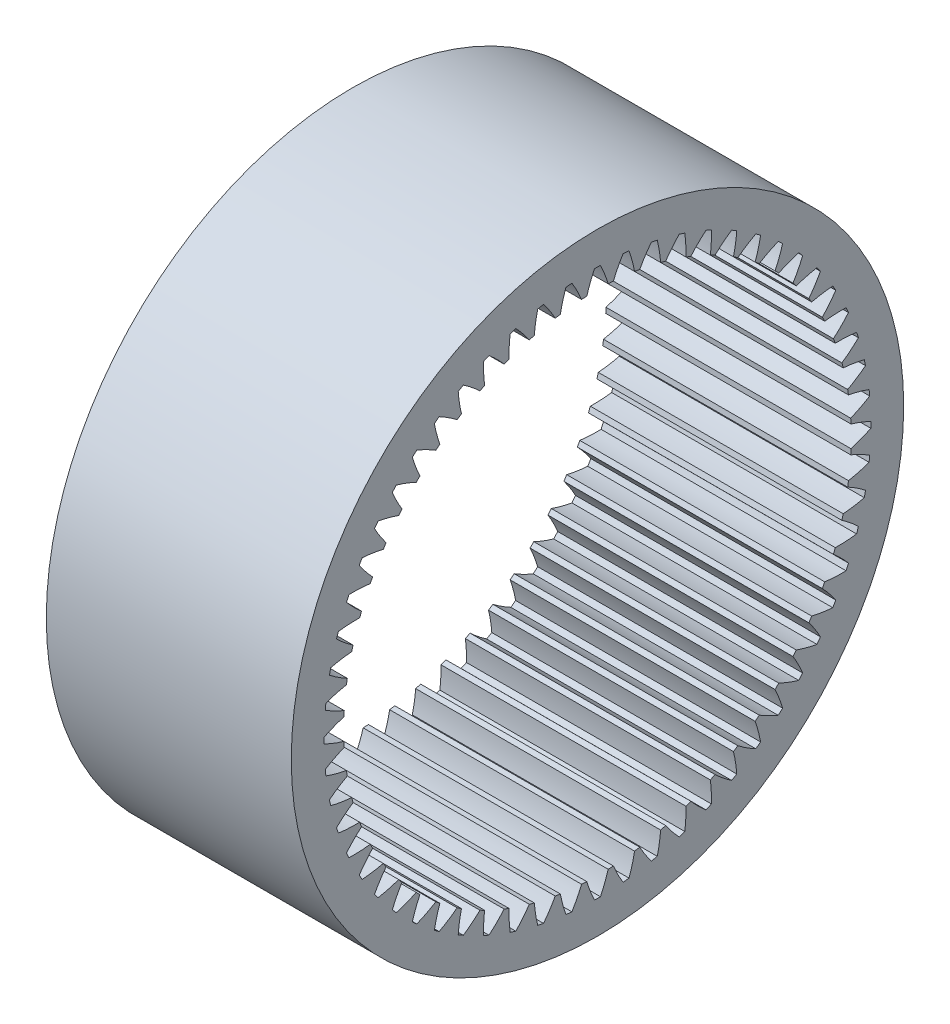
SolidWorks part; units mm, degrees
ref_plane "Plane1" through (0, 0, 0) normal (0, 0, 1) x (1, 0, 0)
ref_plane "Plane2" through (0, 0, 0) normal (0, 1, 0) x (1, 0, 0)
ref_plane "Plane3" through (0, 0, 0) normal (1, 0, 0) x (0, 0, -1)
other "Configuration Table"
sketch "HoldingSke" plane through (0, 0, 0) normal (0, 1, 0) x (1, 0, 0)
  line L0 (0, 0) -> (0.5, -0.866)
  line L1 (-15, 0) -> (100, 0) construction
  line L2 (0, 0) -> (-2.1039, 2.3779)
  line L3 (0, 0) -> (-11.863, 4.5341)
  line L4 (0, 0) -> (4.318, 7.479)
  line L5 (0, 0) -> (-23.7986, -8.8762)
  line L6 (0, 0) -> (-10.5278, -7.1032)
  line L7 (-2.1039, 2.3779) -> (3.3635, 27.1825)
  line L8 (-76.2, 3.3779) -> (-54.61, 3.3779)
  line L9 (-71.009, 38.7566) -> (-53.1078, 45.2721)
  line L10 (-76.2, 71.12) -> (104.1128, 71.12)
  line L11 (0, 0) -> (-28, 0)
  line L12 (-76.2, 101.6) -> (-76.162, 101.6)
  line L13 (24.9733, 27.94) -> (52.9518, 28.4284)
  line L14 (24.9733, 27.94) -> (24.9743, 27.94)
  line L15 (24.9733, 27.94) -> (100.4006, 29.5858)
  circle A0 centre (0, 0) radius 35
  circle A1 centre (0, 0) radius 12.7
  circle A2 centre (0, 0) radius 12.7
  dimension "MHD" = 25.4
  dimension "Hub_dia" = 25.4
  dimension "Diameter" = 70
  dimension "Num_teeth" = 60
  dimension "Pitch" = 1
  dimension "Overall_len" = 25.4
  dimension "Show_teeth" = 60
  dimension "Thickness" = 12.7
  dimension "OAL" = 25.4001
  dimension "T_dim" = 21.59
  dimension "Ap" = 20
  dimension "H" = 19.05
  dimension "Pitch_radius" = 180.3128
  dimension "Width" = 28
  dimension "Backlash" = 0.038
  dimension "Addendum_fac" = 1
  dimension "Dedendum_fac" = 1.25
  dimension "Clearance_fac" = 0.25
  dimension "Dedendum_add" = 0.001
  dimension "Module" = 1
sketch "BasProSke" plane through (0, 0, 0) normal (0, 1, 0) x (1, 0, 0)
  line L0 (-10, 0) -> (60, 0) construction
  line L1 (0, 29) -> (0, 35)
  line L2 (0, 29) -> (28, 29)
  line L3 (28, 29) -> (28, 35)
  line L4 (28, 35) -> (0, 35)
  dimension "Diameter" = 70
  dimension "Thickness" = 28
  dimension "Inside_diameter" = 58
revolve "Base-Revolve" add sketch "BasProSke" angle 360 about L0
sketch "TooCutSke" plane through (0, 0, 0) normal (1, 0, 0) x (0, 0, -1)
  line L3 (0.8803, 29.9871) -> (0.8803, 53.6633) construction
  line L4 (0, 0) -> (0, 59.563) construction
  line L5 (0, 0) -> (-3.576, 68.2339) construction
  line L6 (-13.1633, 24.7167) -> (36.4631, 27.3175) construction
  circle A0 centre (0, 0) radius 30 construction
  circle A1 centre (0, 0) radius 31.251 construction
  circle A2 centre (0, 0) radius 25.3717 construction
  circle A3 centre (0, 0) radius 28.9746 construction
  arc A4 (1.2274, 28.9486) -> (0.3395, 31.2492) centre (-13.1633, 24.7167) ccw
  arc A5 (1.2274, 28.9486) -> (-1.2274, 28.9486) centre (0, 0) ccw
  arc A6 (0.3395, 31.2492) -> (-0.3395, 31.2492) centre (0, 0) ccw
  arc A7 (-0.3395, 31.2492) -> (-1.2274, 28.9486) centre (13.1633, 24.7167) ccw
  dimension "Pitch_dia" = 60
  dimension "Base_dia" = 50.7434
  dimension "Root_dia" = 62.502
  dimension "Overcut_dia" = 57.9492
  dimension "Flank_rad" = 15
  dimension "Half_ang" = 3
  dimension "Half_CT" = 0.8803
extrude "ToothCut" cut sketch "TooCutSke" along normal through all
fillet "Breaks" [suppressed] radius 0.1
fillet "RootFillets" [suppressed] radius 0.251
pattern_circular "TeethCuts" count 60 every 6 about axis through (-10, 0, 0) along (1, 0, 0) of "RootFillets", "Breaks", "ToothCut"
equation "' \"Module@HoldingSke\" = 6.35"
equation "' \"Num_teeth@HoldingSke\" = 24"
equation "' \"Ap@HoldingSke\" =  14.5"
equation "' \"Ap@HoldingSke\" = 14.5"
equation "' \"Width@HoldingSke\" = 12"
equation "' \"Diameter@HoldingSke\" = 8 * 25.4"
equation "' \"Show_teeth@HoldingSke\" = 100"
equation "' \"Backlash@HoldingSke\" = 0.009 * 25.4"
equation "' \"Addendum_fac@HoldingSke\" = 1.0"
equation "' \"Dedendum_fac@HoldingSke\" = 1.25"
equation "' \"Dedendum_add@HoldingSke\" = 0.00005 * 25.4"
equation "' \"Clearance_fac@HoldingSke\" = 0.25"
equation "\"Pitch@HoldingSke\" = 1 / \"Module@HoldingSke\" "
equation "\"Overcut_dia@TooCutSke\" = (\"Num_teeth@HoldingSke\" - 2 * \"Addendum_fac@HoldingSke\") / \"Pitch@HoldingSke\" - 0.002 * 25.4"
equation "\"Pitch_dia@TooCutSke\" = \"Num_teeth@HoldingSke\" / \"Pitch@HoldingSke\""
equation "\"Base_dia@TooCutSke\" = \"Num_teeth@HoldingSke\" / \"Pitch@HoldingSke\" * cos((\"Ap@HoldingSke\"  * 3.14159265 / 180)) * 0.90"
equation "\"Root_dia@TooCutSke\" = \"Num_teeth@HoldingSke\"  / \"Pitch@HoldingSke\" + 2 *  \"Dedendum_fac@HoldingSke\"/ \"Pitch@HoldingSke\" + \"Dedendum_add@HoldingSke\" * 2"
equation "\"Half_ang@TooCutSke\" = 180 / \"Num_teeth@HoldingSke\""
equation "\"Half_CT@TooCutSke\" = \"Num_teeth@HoldingSke\" / \"Pitch@HoldingSke\" * sin((3.14159265 / 2 / \"Num_teeth@HoldingSke\")) / 2 + 10 * \"Backlash@HoldingSke\" / 4"
equation "\"Flank_rad@TooCutSke\" = \"Num_teeth@HoldingSke\" / \"Pitch@HoldingSke\" / 4"
equation "\"Radius@RootFillets\"= \"Clearance_fac@HoldingSke\" / \"Pitch@HoldingSke\" + \"Dedendum_add@HoldingSke\""
equation "\"Break_rad@Breaks\" = 0.02 / \"Pitch@HoldingSke\" * 5"
equation "\"Num_teeth@TeethCuts\" = int( \"Show_teeth@HoldingSke\" ) + 1"
equation "\"Num_teeth@TeethCuts\" = ((sgn( \"Num_teeth@TeethCuts\" - \"Num_teeth@HoldingSke\" )-1)*( \"Num_teeth@TeethCuts\" - \"Num_teeth@HoldingSke\" ))/-2+ \"Num_teeth@HoldingSke\""
equation "\"Num_teeth@TeethCuts\" = ((sgn( \"Num_teeth@TeethCuts\" - 2.0)+1)*( \"Num_teeth@TeethCuts\" - 2.0))/2 +2.0"
equation "\"Angle@TeethCuts\" = 360.0 / \"Num_teeth@HoldingSke\""
equation "\"Diameter@BasProSke\" = \"Num_teeth@HoldingSke\"  / \"Pitch@HoldingSke\" + 2 *  \"Dedendum_fac@HoldingSke\"/ \"Pitch@HoldingSke\" + \"Dedendum_add@HoldingSke\" * 2 + 0.002 * 25.4"
equation "\"Diameter@BasProSke\" = ((sgn( \"Diameter@BasProSke\"  - \"Diameter@HoldingSke\" )+1)*( \"Diameter@BasProSke\"  - \"Diameter@HoldingSke\" ))/2 + \"Diameter@HoldingSke\""
equation "\"Inside_diameter@BasProSke\" =  (\"Num_teeth@HoldingSke\" - 2 * \"Addendum_fac@HoldingSke\") / \"Pitch@HoldingSke\" "
equation "\"Thickness@BasProSke\"  = \"Width@HoldingSke\""
